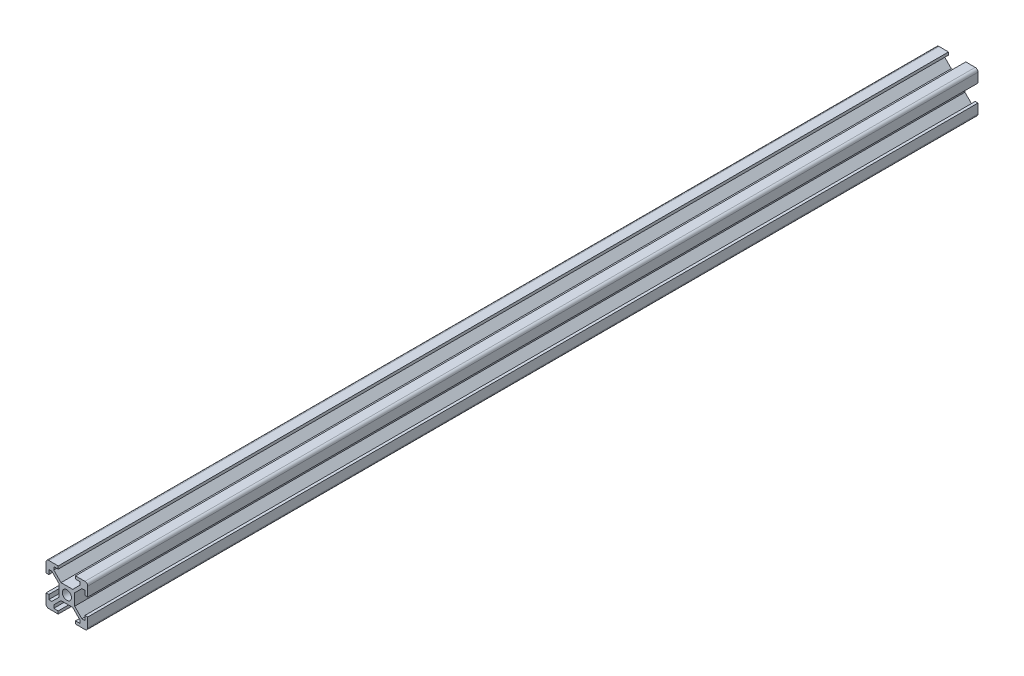
SolidWorks part; units mm, degrees
ref_plane "前视基准面" through (0, 0, 0) normal (0, 0, 1) x (1, 0, 0)
ref_plane "上视基准面" through (0, 0, 0) normal (0, 1, 0) x (1, 0, 0)
ref_plane "右视基准面" through (0, 0, 0) normal (1, 0, 0) x (0, 0, -1)
sketch "草图2" plane through (0, 0, 0) normal (0, 0, 1) x (1, 0, 0)
  line L1 (-2.0929, -2.8) -> (-4.7, -5.4071)
  line L2 (2.8, -2.0929) -> (2.8, 2.0929)
  line L3 (2.8, 2.0929) -> (5.4071, 4.7)
  line L4 (5.4071, 4.7) -> (6.5, 4.7)
  line L5 (6.5, 4.7) -> (6.5, 3.1)
  line L6 (6.5, 3.1) -> (7.5, 3.1)
  line L7 (7.5, 3.1) -> (7.5, 6.5)
  line L8 (-2.8, -2.0929) -> (-5.4071, -4.7)
  line L9 (-2.0929, 2.8) -> (2.0929, 2.8)
  line L10 (3.1, 7.5) -> (6.5, 7.5)
  line L11 (3.1, 6.5) -> (3.1, 7.5)
  line L12 (4.7, 6.5) -> (3.1, 6.5)
  line L13 (4.7, 5.4071) -> (4.7, 6.5)
  line L14 (2.0929, 2.8) -> (4.7, 5.4071)
  line L15 (-5.4071, 4.7) -> (-6.5, 4.7)
  line L16 (-6.5, 4.7) -> (-6.5, 3.1)
  line L17 (-6.5, 3.1) -> (-7.5, 3.1)
  line L18 (-7.5, 3.1) -> (-7.5, 6.5)
  line L19 (-4.7, 6.5) -> (-3.1, 6.5)
  line L20 (-3.1, 6.5) -> (-3.1, 7.5)
  line L21 (-3.1, 7.5) -> (-6.5, 7.5)
  line L22 (-4.7, 5.4071) -> (-4.7, 6.5)
  line L23 (-2.8, 2.0929) -> (-5.4071, 4.7)
  line L24 (-2.8, -2.0929) -> (-2.8, 2.0929)
  line L25 (-2.0929, 2.8) -> (-4.7, 5.4071)
  line L26 (-4.7, -5.4071) -> (-4.7, -6.5)
  line L27 (-3.1, -7.5) -> (-6.5, -7.5)
  line L28 (-3.1, -6.5) -> (-3.1, -7.5)
  line L29 (-4.7, -6.5) -> (-3.1, -6.5)
  line L30 (-7.5, -3.1) -> (-7.5, -6.5)
  line L31 (-6.5, -3.1) -> (-7.5, -3.1)
  line L32 (-6.5, -4.7) -> (-6.5, -3.1)
  line L33 (-5.4071, -4.7) -> (-6.5, -4.7)
  line L34 (2.0929, -2.8) -> (4.7, -5.4071)
  line L35 (4.7, -5.4071) -> (4.7, -6.5)
  line L36 (4.7, -6.5) -> (3.1, -6.5)
  line L37 (3.1, -6.5) -> (3.1, -7.5)
  line L38 (3.1, -7.5) -> (6.5, -7.5)
  line L39 (-2.0929, -2.8) -> (2.0929, -2.8)
  line L40 (7.5, -3.1) -> (7.5, -6.5)
  line L41 (6.5, -3.1) -> (7.5, -3.1)
  line L42 (6.5, -4.7) -> (6.5, -3.1)
  line L43 (5.4071, -4.7) -> (6.5, -4.7)
  line L44 (2.8, -2.0929) -> (5.4071, -4.7)
  arc A0 (7.5, 6.5) -> (6.5, 7.5) centre (6.5, 6.5) ccw
  arc A1 (-7.5, 6.5) -> (-6.5, 7.5) centre (-6.5, 6.5) cw
  arc A2 (-7.5, -6.5) -> (-6.5, -7.5) centre (-6.5, -6.5) ccw
  arc A3 (7.5, -6.5) -> (6.5, -7.5) centre (6.5, -6.5) cw
  circle A4 centre (0, 0) radius 1.65
  point P3 (0, -2.8)
  point P21 (7.5, 7.5)
  point P36 (0, 2.8)
  point P43 (-2.8, 0)
  point P60 (2.8, 0)
  point P61 (7.5, -7.5)
  dimension "D9" = 1
  dimension "D1" = 3.3
  dimension "D5" = 1
  dimension "D8" = 1
extrude "凸台-拉伸1" add sketch "草图2" along normal mid plane 320
